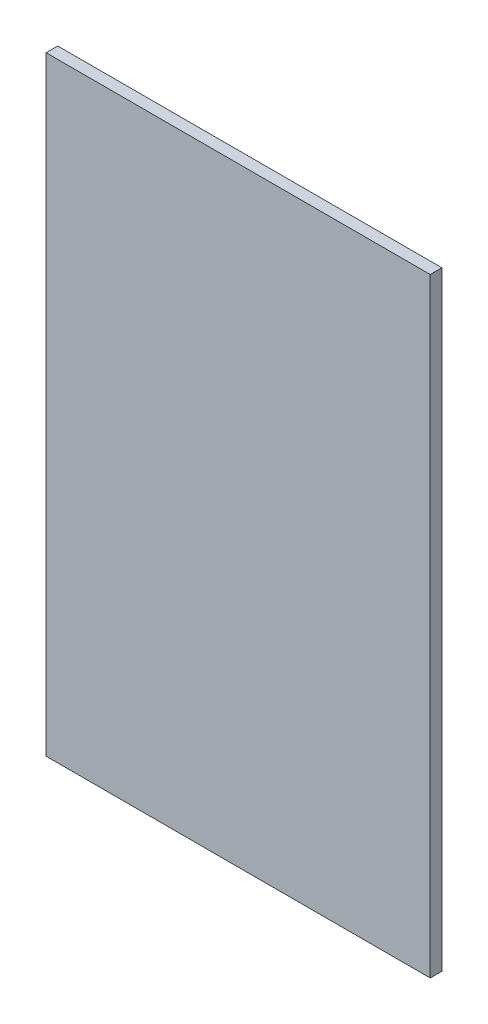
SolidWorks part; units mm, degrees
material "Balsa"
ref_plane "Plan de face" through (0, 0, 0) normal (0, 0, 1) x (1, 0, 0)
ref_plane "Plan de dessus" through (0, 0, 0) normal (0, 1, 0) x (1, 0, 0)
ref_plane "Plan de droite" through (0, 0, 0) normal (1, 0, 0) x (0, 0, -1)
sketch "Esquisse1" plane through (0, 0, 0) normal (0, 0, 1) x (1, 0, 0)
  line L1 (0, 0) -> (725, 0)
  line L2 (0, 0) -> (0, 1150)
  line L3 (0, 1150) -> (725, 1150)
  line L4 (725, 0) -> (725, 1150)
  dimension "D1" = 725
  dimension "D2" = 1150
extrude "Boss.-Extru.1" add sketch "Esquisse1" along normal blind 22
